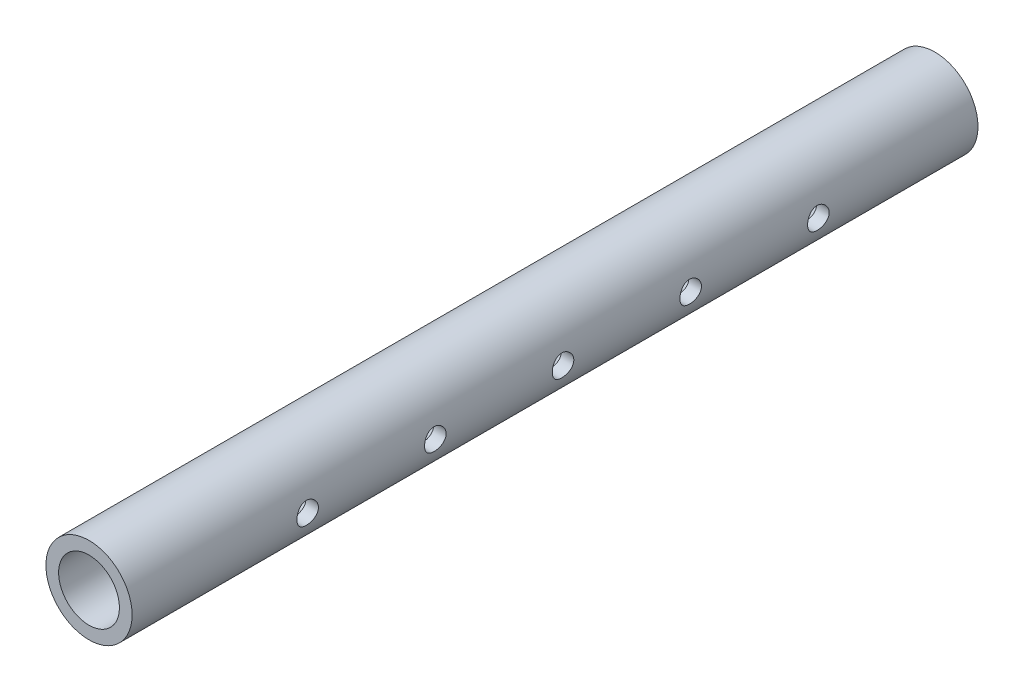
SolidWorks part; units mm, degrees
material "PVC Rigid"
ref_plane "Front Plane" through (0, 0, 0) normal (0, 0, 1) x (1, 0, 0)
ref_plane "Top Plane" through (0, 0, 0) normal (0, 1, 0) x (1, 0, 0)
ref_plane "Right Plane" through (0, 0, 0) normal (1, 0, 0) x (0, 0, -1)
sketch "Sketch1" plane through (0, 0, 0) normal (0, 0, 1) x (1, 0, 0)
  circle A0 centre (0, 0) radius 9.525
  circle A1 centre (0, 0) radius 13.5
  dimension "D1" = 27
  dimension "D2" = 19.05
sketch3d "3DSketch1"
  line L0 (0, 0, 0) -> (0, 0, -265)
  dimension "D1" = 265
sweep "Sweep1" add profiles "Sketch1" path "3DSketch1"
ref_plane "Plane1" through (13.5, 0, 0) normal (1, 0, 0) x (0, 0, -1)
sketch "Sketch5" plane through (13.5, 0, 0) normal (1, 0, 0) x (0, 0, -1)
  line L2 (265, -13.5) -> (265, 13.5) construction
  point P0 (55, 0)
  point P1 (95, 0)
  point P2 (135, 0)
  point P3 (175, 0)
  point P4 (0, 0)
  point P6 (0, 0)
  point P7 (215, 0)
  dimension "D1" = 55
  dimension "D2" = 40
  dimension "D3" = 40
  dimension "D4" = 40
  dimension "D5" = 40
  dimension "D6" = 50
hole_wizard "1/4 Clearance Hole2" positions "3DSketch4" profile "Sketch6" hole size "1/4" standard "ANSI Inch" end condition up to next
sketch3d "3DSketch4"
  point P0 (13.5, 0, -55)
  point P3 (13.5, 0, -95)
  point P6 (13.5, 0, -135)
  point P9 (13.5, 0, -175)
  point P13 (13.5, 0, -55)
  point P15 (13.5, 0, -95)
  point P17 (13.5, 0, -135)
  point P19 (13.5, 0, -175)
  point P26 (13.5, 0, -215)
  point P29 (0, 0, 0)
sketch "Sketch6" plane through (13.5, 0, -215) normal (0, 1, 0) x (0, 0, -1)
  line L0 (0, 0) -> (0, 13.5)
  line L1 (0, 13.5) -> (3.3782, 13.5)
  line L2 (3.3782, 13.5) -> (3.3782, 0)
  line L5 (3.3782, 0) -> (0, 0)
  line L11 (0, -6.35) -> (0, 107.95) construction
  dimension "Thru Hole Dia." = 6.7564
  dimension "Thru Hole Depth" = 13.5
